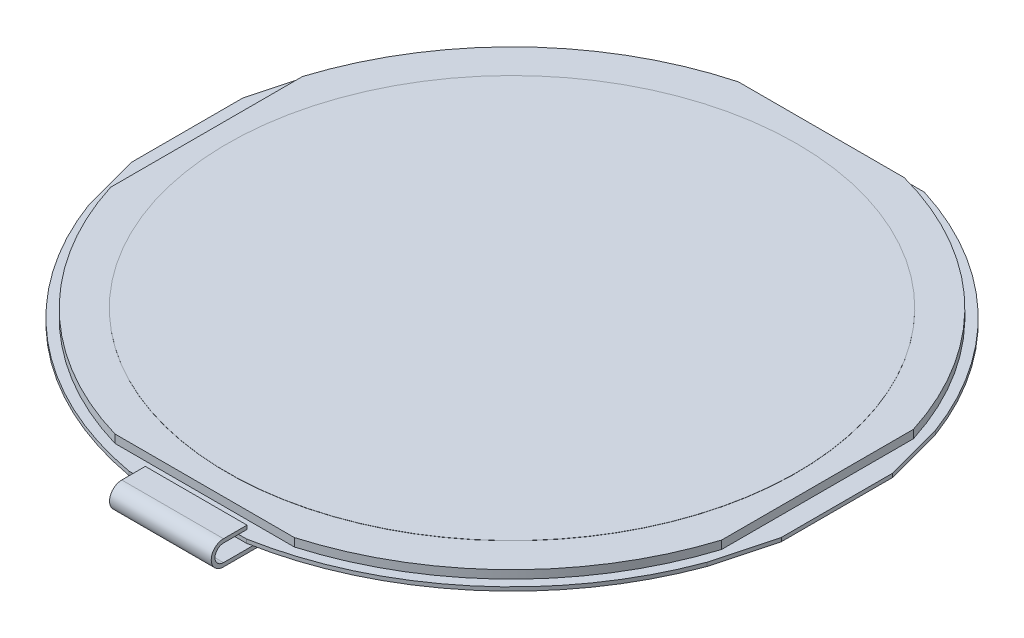
SolidWorks part; units mm, degrees
ref_plane "Front Plane" through (0, 0, 0) normal (0, 0, 1) x (1, 0, 0)
ref_plane "Top Plane" through (0, 0, 0) normal (0, 1, 0) x (1, 0, 0)
ref_plane "Right Plane" through (0, 0, 0) normal (1, 0, 0) x (0, 0, -1)
sketch "Sketch1" plane through (0, 0, 0) normal (0, 1, 0) x (1, 0, 0)
  line L0 (-30.0156, 0) -> (32.7382, 0) construction
  line L1 (0, 27.5905) -> (0, -29.5611) construction
  line L2 (17.25, 2.9475) -> (17.25, -2.9475)
  line L3 (17.25, 2.9475) -> (16.4127, 6.0724)
  line L4 (-5.1665, 16.72) -> (5.1665, 16.72)
  line L5 (17.25, -2.9475) -> (16.4127, -6.0724)
  line L6 (-17.25, 2.9475) -> (-17.25, -2.9475)
  line L7 (-17.25, -2.9475) -> (-16.4127, -6.0724)
  line L8 (-17.25, 2.9475) -> (-16.4127, 6.0724)
  line L9 (-3.1178, -17.22) -> (3.1178, -17.22)
  arc A0 (-5.1665, 16.72) -> (-16.4127, 6.0724) centre (0, 0) ccw
  circle A1 centre (0, 0) radius 15.12 construction
  arc A2 (16.4127, 6.0724) -> (5.1665, 16.72) centre (0, 0) ccw
  arc A3 (-16.4127, -6.0724) -> (-3.1178, -17.22) centre (0, 0) ccw
  arc A4 (3.1178, -17.22) -> (16.4127, -6.0724) centre (0, 0) ccw
  point P10 (17.25, 0)
  point P14 (0, 16.72)
  point P22 (0, -17.22)
  dimension "D1" = 35
  dimension "D3" = 30.24
  dimension "D5" = 165
  dimension "D2" = 5.895
  dimension "D4" = 10.333
  dimension "D6" = 17.25
  dimension "D7" = 33.94
extrude "Boss-Extrude1" add sketch "Sketch1" along normal blind 0.2
sketch "Sketch2" plane through (0, 0.2, 0) normal (0, 1, 0) x (1, 0, 0)
  line L0 (0, 22.8644) -> (0, -34.2978) construction
  line L1 (-37.6792, 0) -> (47.9465, 0) construction
  line L2 (-4.4028, 16.42) -> (4.4028, 16.42)
  line L3 (5.1665, 16.72) -> (-5.1665, 16.72) construction
  line L4 (-4.7599, -16.32) -> (4.7599, -16.32)
  line L5 (-3.1178, -17.22) -> (3.1178, -17.22) construction
  line L6 (-16.22, 5.0903) -> (-16.22, -5.0903)
  line L7 (16.22, 5.0903) -> (16.22, -5.0903)
  arc A0 (-4.4028, 16.42) -> (-16.22, 5.0903) centre (0, 0) ccw
  arc A1 (4.7599, -16.32) -> (16.22, -5.0903) centre (0, 0) ccw
  arc A2 (-16.22, -5.0903) -> (-4.7599, -16.32) centre (0, 0) ccw
  arc A3 (16.22, 5.0903) -> (4.4028, 16.42) centre (0, 0) ccw
  point P10 (0, 16.42)
  point P14 (0, -16.32)
  point P19 (-16.22, 0)
  dimension "D1" = 34
  dimension "D2" = 0.3
  dimension "D3" = 0.9
  dimension "D4" = 16.22
extrude "Boss-Extrude5" add sketch "Sketch2" along normal blind 0.435
sketch "Sketch5" plane through (0, 0.635, 0) normal (0, 1, 0) x (1, 0, 0)
  circle A0 centre (0, 0) radius 15.12
  dimension "D1" = 30.24
extrude "Boss-Extrude6" add sketch "Sketch5" along normal blind 0.01
pattern_linear "LPattern1" count 2 spacing 0.4 along (0, -1, 0) of "Boss-Extrude5"
sketch "Sketch6" plane through (0, 0, 0) normal (-1, 0, 0) x (0, 0, 1)
  line L1 (17.22, 0.2) -> (18.02, 0.2)
  line L4 (18.02, -0.9) -> (-0.78, -0.9)
  line L9 (18.02, 0.2) -> (18.02, -1.1193) construction
  line L10 (18.02, -0.7) -> (-0.78, -0.7)
  line L11 (18.02, 0.4) -> (16.77, 0.4)
  line L12 (16.77, 0.4) -> (16.77, 0.2)
  line L13 (17.22, 0.2) -> (6.0724, 0.2) construction
  line L14 (16.77, 0.2) -> (17.22, 0.2)
  line L15 (-0.78, -0.9) -> (-0.78, -0.7)
  arc A2 (18.02, -0.7) -> (18.02, 0.2) centre (18.02, -0.25) ccw
  arc A3 (18.02, -0.9) -> (18.02, 0.4) centre (18.02, -0.25) ccw
  dimension "D1" = 0.8
  dimension "D5" = 18.8
  dimension "D2" = 0.9
  dimension "D3" = 1.3
  dimension "D4" = 1.25
extrude "Boss-Extrude7" add sketch "Sketch6" along normal mid plane 5.4
